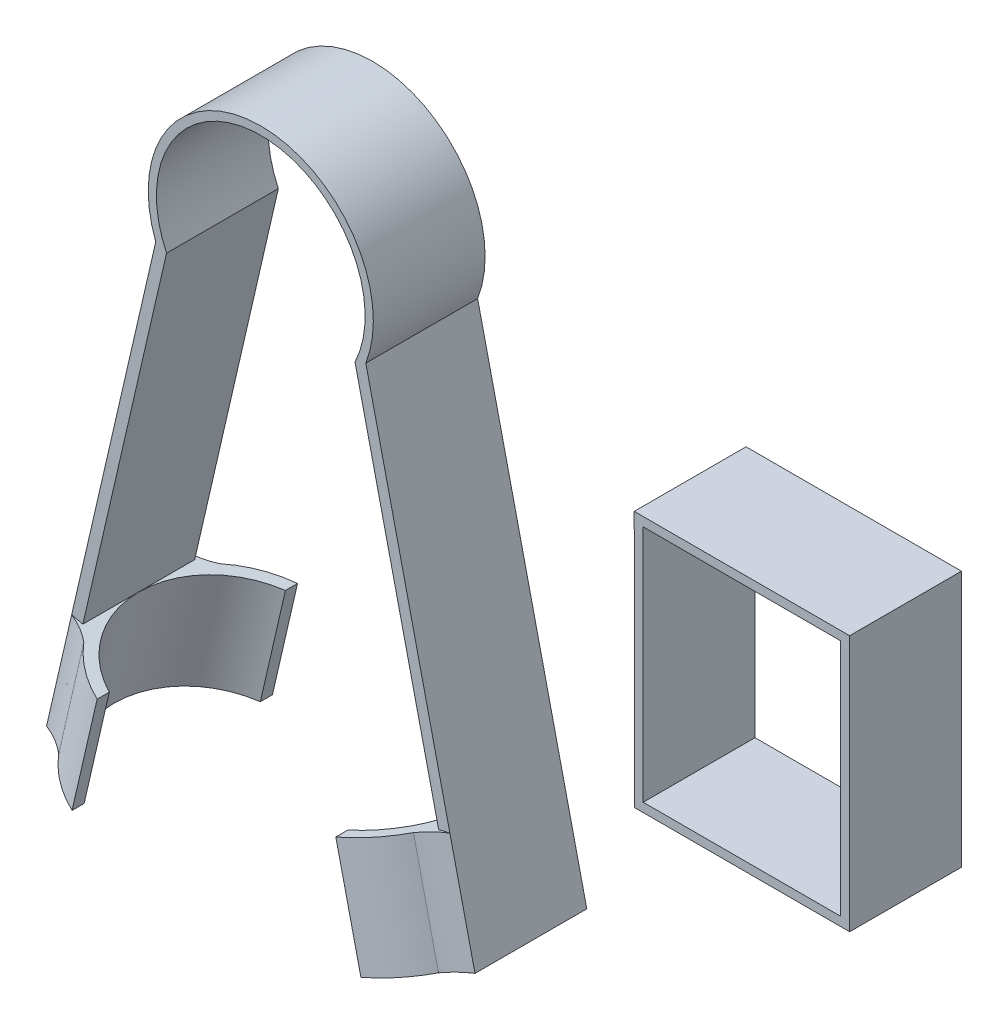
SolidWorks part; units mm, degrees
ref_plane "Front Plane" through (0, 0, 0) normal (0, 0, 1) x (1, 0, 0)
ref_plane "Top Plane" through (0, 0, 0) normal (0, 1, 0) x (1, 0, 0)
ref_plane "Right Plane" through (0, 0, 0) normal (1, 0, 0) x (0, 0, -1)
sketch "Sketch1" plane through (0, 0, 0) normal (0, 0, 1) x (1, 0, 0)
  line L0 (3.6876, 24.1043) -> (3.6876, -63.8761) construction
  line L1 (16.3306, -2.4335) -> (27.5549, -51.1573)
  line L2 (17.74, -1.6674) -> (29.0609, -50.8104)
  line L3 (27.5549, -51.1573) -> (29.0609, -50.8104)
  line L4 (-8.9554, -2.4335) -> (-20.1798, -51.1573)
  line L5 (-21.6858, -50.8104) -> (-20.1798, -51.1573)
  line L6 (-10.3649, -1.6674) -> (-21.6858, -50.8104)
  line L9 (3.6306, -2.4335) -> (16.3306, -2.4335) construction
  arc A0 (16.3306, -2.4335) -> (-8.9554, -2.4335) centre (3.6876, 3.5794) ccw
  arc A3 (17.7805, -1.8429) -> (-10.4053, -1.8429) centre (3.6876, 3.5794) ccw
  dimension "D1" = 28
  dimension "D3" = 50
  dimension "D4" = 12.7
  dimension "D5" = 30.2
extrude "Boss-Extrude1" add sketch "Sketch1" along normal blind 15
sketch "Sketch2" plane through (12.5796, -54.6071, 0) normal (0.2245, -0.9745, 0) x (0.9745, 0.2245, 0)
  line L0 (16.913, 15) -> (16.913, 0) construction
  line L1 (16.913, 0) -> (16.913, 7.5) construction
  line L2 (16.913, 7.5) -> (15.3675, 7.5) construction
  line L3 (7.3065, -4.3191) -> (7.3065, -5.9444)
  line L6 (16.359, 7.5) -> (16.913, 7.5) construction
  line L8 (7.3065, 20.9444) -> (7.3065, 19.3191)
  arc A11 (7.3065, -4.3191) -> (7.3065, 19.3191) centre (2.659, 7.5) ccw
  arc A12 (7.3065, -5.9444) -> (13.5672, -1.6302) centre (2.659, 7.5) ccw
  arc A13 (13.5672, 16.6302) -> (7.3065, 20.9444) centre (2.659, 7.5) ccw
  spline S0 degree 2 poles (16.913, 15) (15.0698, 15.4531) (13.5672, 16.6302) knots 0 0 0 1 1 1
  spline S1 degree 2 poles (16.913, 0) (15.0698, -0.4531) (13.5672, -1.6302) knots 0 0 0 1 1 1
  line M1 (15.3675, 0) -> (16.913, 0)
  line M2 (16.913, 0) -> (16.913, 15)
  line M3 (16.913, 15) -> (15.3675, 15)
  line M4 (15.3675, 15) -> (15.3675, 0)
extrude "Boss-Extrude2" add sketch "Sketch2" along normal blind 15 contours S1 S0 A13 L8 A11 L3 A12 M1 M4 M3 | M4 M1 M2 M3
sketch "Sketch3" plane through (-12.208, -52.9938, 0) normal (-0.2245, -0.9745, 0) x (0.9745, -0.2245, 0)
  line L0 (-9.726, 15) -> (-9.726, 0) construction
  line L1 (-9.726, 0) -> (-8.1806, 0) construction
  line L2 (-8.1806, 0) -> (-8.1806, 15) construction
  line L3 (-8.1806, 15) -> (-9.726, 15) construction
  line L4 (-9.726, 15) -> (-9.726, 7.5) construction
  line L5 (-9.726, 7.5) -> (-8.1806, 7.5) construction
  line L6 (-9.726, 0) -> (-9.726, 15) construction
  line L7 (-9.726, 15) -> (-9.726, 7.5) construction
  line L8 (-9.726, 7.5) -> (-8.1806, 7.5) construction
  line L9 (-0.1195, 19.3191) -> (-0.1195, 20.9444)
  line L10 (-9.172, 7.5) -> (-9.726, 7.5) construction
  line L11 (-0.1195, -5.9444) -> (-0.1195, -4.3191)
  arc A0 (-0.1195, 19.3191) -> (-0.1195, -4.3191) centre (4.528, 7.5) ccw
  arc A1 (-0.1195, 20.9444) -> (-6.3803, 16.6302) centre (4.528, 7.5) ccw
  arc A2 (-6.3803, -1.6302) -> (-0.1195, -5.9444) centre (4.528, 7.5) ccw
  spline S0 degree 2 poles (-9.726, 0) (-7.8828, -0.4531) (-6.3803, -1.6302) knots 0 0 0 1 1 1
  spline S1 degree 2 poles (-9.726, 15) (-7.8828, 15.4531) (-6.3803, 16.6302) knots 0 0 0 1 1 1
  line M1 (-9.726, 0) -> (-8.1806, 0)
  line M2 (-8.1806, 0) -> (-8.1806, 15)
  line M3 (-8.1806, 15) -> (-9.726, 15)
  line M4 (-9.726, 15) -> (-9.726, 0)
extrude "Boss-Extrude3" add sketch "Sketch3" along normal blind 15 contours M4 M1 M2 M3 | S1 S0 A2 L11 A0 L9 A1 M3 M2 M1
sketch "Sketch4" plane through (0, 0, 0) normal (0, 0, 1) x (1, 0, 0)
  line L0 (54.9915, -2.2578) -> (81.4915, -2.2578) construction
  line L1 (54.9915, -2.2578) -> (81.4915, -2.2578)
  line L2 (54.9915, -2.2578) -> (54.9915, -34.2578)
  line L3 (54.9915, -34.2578) -> (81.4915, -34.2578)
  line L4 (81.4915, -2.2578) -> (81.4915, -34.2578)
  line L5 (68.2415, -2.2578) -> (68.2415, -34.2578) construction
  line L6 (68.2415, -34.2578) -> (68.2415, -18.2578) construction
  line L8 (53.7915, -1.0579) -> (82.6915, -1.0579)
  line L9 (53.7915, -1.0579) -> (53.8325, -35.4578)
  line L10 (53.8325, -35.4578) -> (82.6915, -35.4578)
  line L11 (82.6915, -1.0579) -> (82.6915, -35.4578)
  line L12 (68.262, -35.4578) -> (68.2415, -1.0578) construction
  line L13 (53.812, -18.2578) -> (82.6915, -18.2578) construction
  dimension "D1" = 32
  dimension "D2" = 26.5
  dimension "D3" = 34.4
  dimension "D4" = 28.9
extrude "Boss-Extrude4" add sketch "Sketch4" along normal blind 15 separate body
